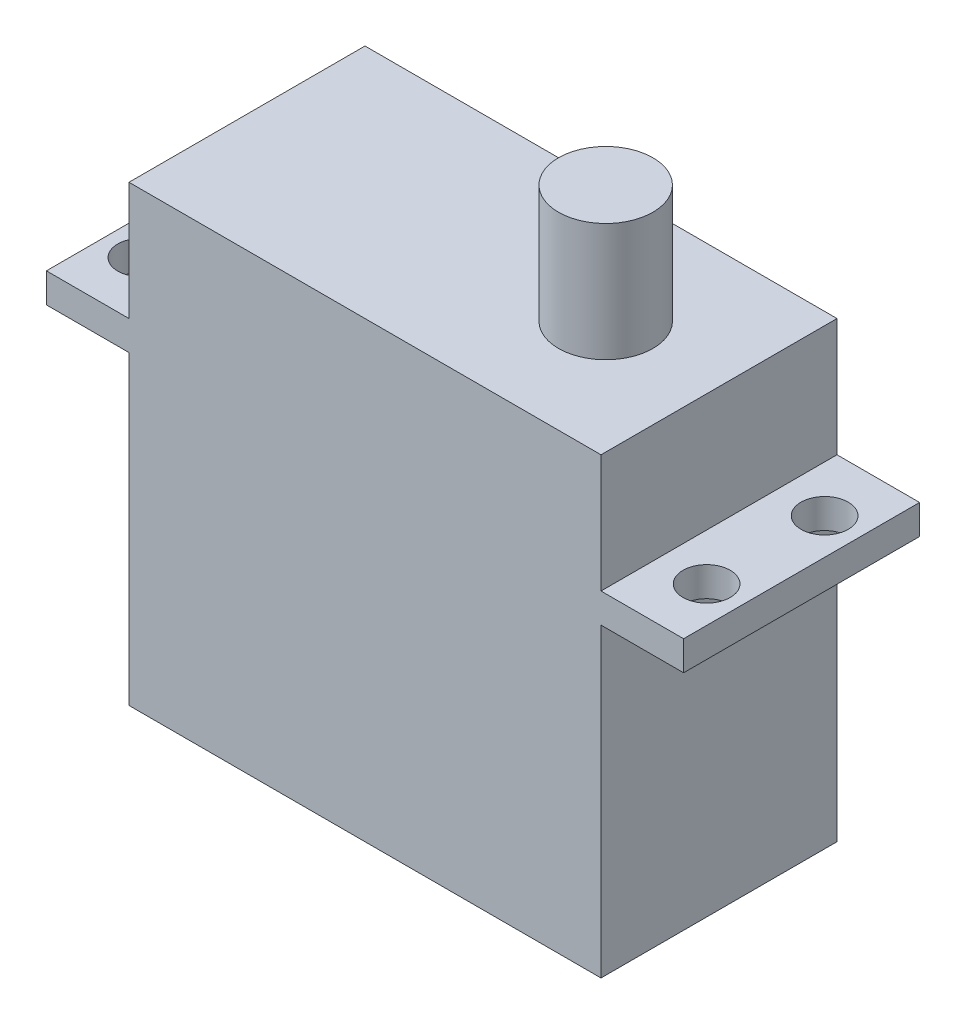
SolidWorks part; units mm, degrees
ref_plane "Front Plane" through (0, 0, 0) normal (0, 0, 1) x (1, 0, 0)
ref_plane "Top Plane" through (0, 0, 0) normal (0, 1, 0) x (1, 0, 0)
ref_plane "Right Plane" through (0, 0, 0) normal (1, 0, 0) x (0, 0, -1)
sketch "Sketch1" plane through (0, 0, 0) normal (0, 1, 0) x (1, 0, 0)
  line L1 (-20, 10) -> (20, 10)
  line L2 (-20, 10) -> (-20, -10)
  line L3 (-20, -10) -> (20, -10)
  line L4 (20, 10) -> (20, -10)
  line L5 (-20, 10) -> (20, -10) construction
  line L6 (-20, -10) -> (20, 10) construction
  point P0 (0, 0)
extrude "Boss-Extrude1" add sketch "Sketch1" along normal blind 25.9
sketch "Sketch2" plane through (0, 25.9, 0) normal (0, 1, 0) x (1, 0, 0)
  line L0 (0, 0) -> (23.95, 0)
  line L1 (0, 0) -> (-23.95, 0)
  line L2 (-23.95, 0) -> (-23.95, 5)
  line L3 (-23.95, 0) -> (-23.95, -5)
  line L4 (23.95, 0) -> (23.95, 5)
  line L5 (23.95, 0) -> (23.95, -5)
  line L7 (-27, 10) -> (27, 10)
  line L8 (-27, 10) -> (-27, -10)
  line L9 (-27, -10) -> (27, -10)
  line L10 (27, 10) -> (27, -10)
  line L11 (-27, 10) -> (27, -10) construction
  line L12 (-27, -10) -> (27, 10) construction
  circle A0 centre (-23.95, 5) radius 2
  circle A1 centre (-23.95, -5) radius 2
  circle A2 centre (23.95, 5) radius 2
  circle A3 centre (23.95, -5) radius 2
extrude "Boss-Extrude2" add sketch "Sketch2" along normal blind 2.5
sketch "Sketch3" plane through (0, 28.4, 0) normal (0, 1, 0) x (1, 0, 0)
  line L0 (-27, -10) -> (27, -10) construction
  line L1 (-20, 10) -> (20, 10)
  line L2 (-20, 10) -> (-20, -10)
  line L3 (-20, -10) -> (20, -10)
  line L4 (20, 10) -> (20, -10)
  line L5 (-20, 10) -> (20, -10) construction
  line L6 (-20, -10) -> (20, 10) construction
  point P0 (0, 0)
extrude "Boss-Extrude3" add sketch "Sketch3" along normal blind 10
sketch "Sketch4" plane through (0, 38.4, 0) normal (0, 1, 0) x (1, 0, 0)
  line L0 (20, 0) -> (10.4, 0)
  line L1 (20, -10) -> (20, 10) construction
  circle A0 centre (10.4, 0) radius 4
extrude "Boss-Extrude4" add sketch "Sketch4" along normal blind 10
